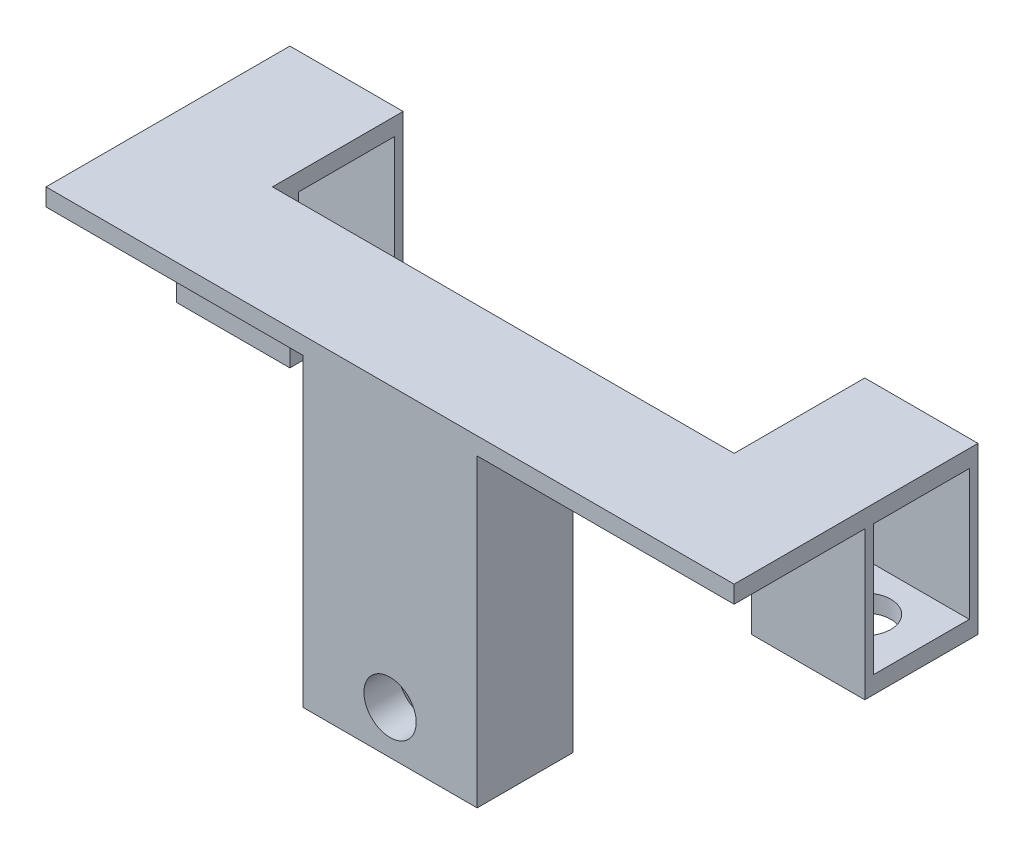
SolidWorks part; units mm, degrees
ref_plane "Front Plane" through (0, 0, 0) normal (0, 0, 1) x (1, 0, 0)
ref_plane "Top Plane" through (0, 0, 0) normal (0, 1, 0) x (1, 0, 0)
ref_plane "Right Plane" through (0, 0, 0) normal (1, 0, 0) x (0, 0, -1)
sketch "ｽｹｯﾁ2" plane through (0, 0, 0) normal (0, 1, 0) x (1, 0, 0)
  line L0 (6.5, 13) -> (6.5, 0) construction
  line L1 (0, 0) -> (13, 0)
  line L2 (0, 0) -> (0, 13)
  line L3 (0, 13) -> (13, 13)
  line L4 (13, 0) -> (13, 13)
  line L9 (39.5, 31.8136) -> (39.5, -25.5918) construction
  line L10 (0, 6.5) -> (13, 6.5) construction
  line L11 (79, 13) -> (66, 13)
  line L12 (66, 0) -> (66, 13)
  line L13 (79, 0) -> (66, 0)
  line L14 (79, 0) -> (79, 13)
  circle A2 centre (6.5, 6.5) radius 3
  circle A3 centre (72.5, 6.5) radius 3
  dimension "D5" = 6
  dimension "D1" = 13
  dimension "D2" = 13
  dimension "D3" = 33
extrude "ﾎﾞｽ - 押し出し1" add sketch "ｽｹｯﾁ2" along normal blind 2
sketch "ｽｹｯﾁ3" plane through (0, 2, 0) normal (0, 1, 0) x (1, 0, 0)
  line L0 (13, 0) -> (13, 13) construction
  line L1 (0, 13) -> (13, 13)
  line L2 (0, 13) -> (0, 12)
  line L3 (0, 12) -> (13, 12)
  line L4 (13, 13) -> (13, 12)
  line L5 (0, 6.5) -> (79, 6.5) construction
  line L6 (0, 13) -> (0, 0) construction
  line L7 (79, 0) -> (79, 13) construction
  line L8 (39.5, 6.5) -> (39.5, 29.5661) construction
  line L9 (0, 1) -> (13, 1)
  line L10 (13, 0) -> (13, 1)
  line L11 (0, 0) -> (13, 0)
  line L12 (0, 0) -> (0, 1)
  line L13 (79, 0) -> (79, 1)
  line L14 (79, 0) -> (66, 0)
  line L15 (66, 0) -> (66, 1)
  line L16 (79, 1) -> (66, 1)
  line L17 (79, 12) -> (66, 12)
  line L18 (66, 13) -> (66, 12)
  line L19 (79, 13) -> (66, 13)
  line L20 (79, 13) -> (79, 12)
  dimension "D1" = 1
extrude "ﾎﾞｽ - 押し出し2" add sketch "ｽｹｯﾁ3" along normal blind 15
sketch "ｽｹｯﾁ4" plane through (0, 17, 0) normal (0, 1, 0) x (1, 0, 0)
  line L0 (0, 13) -> (0, 0)
  line L1 (0, 0) -> (0, -15)
  line L2 (79, 13) -> (79, 0)
  line L3 (79, 0) -> (79, -15)
  line L4 (79, -15) -> (0, -15)
  line L5 (13, 0) -> (13, -2)
  line L6 (66, 0) -> (66, -2)
  line L7 (66, -2) -> (13, -2)
  line L8 (13, 0) -> (13, 13)
  line L9 (66, 1) -> (66, 12)
  line L10 (79, 13) -> (66, 13)
  line L11 (66, 13) -> (66, 12)
  line L12 (0, 13) -> (13, 13)
  line L14 (0, -15) -> (13, -15)
  line L15 (0, -15) -> (0, 13)
  line L16 (0, 13) -> (13, 13)
  line L17 (13, -15) -> (13, 13)
  line L18 (79, 13) -> (66, 13)
  line L19 (79, 13) -> (79, -15)
  line L20 (79, -15) -> (66, -15)
  line L21 (66, 13) -> (66, -15)
  line L22 (66, -2) -> (13, -2)
  line L23 (66, -2) -> (66, -15)
  line L24 (66, -15) -> (13, -15)
  line L25 (13, -2) -> (13, -15)
  line M6 (0, 1) -> (0, 0)
  line M7 (0, 0) -> (13, 0)
  line M8 (13, 0) -> (13, 1)
  line M9 (13, 1) -> (0, 1)
  dimension "D1" = 15
  dimension "D2" = 2
extrude "ﾎﾞｽ - 押し出し3" add sketch "ｽｹｯﾁ4" along normal blind 2 contours L4 L17 L5 L1 M7 | L12 L0 L8 M9 | M9 M6 M7 M8 | L21 L7 L17 L4 | L9 L21 L6 L4 L3 L2 L10 L11
sketch "ｽｹｯﾁ5" plane through (0, 17, 0) normal (0, -1, 0) x (1, 0, 0)
  line L0 (66, 2) -> (13, 2) construction
  line L1 (49.5, 2) -> (29.5, 2)
  line L2 (49.5, 2) -> (49.5, 15)
  line L3 (49.5, 15) -> (29.5, 15)
  line L4 (29.5, 2) -> (29.5, 15)
  line L5 (79, 15) -> (0, 15) construction
  line L7 (49.5, 15) -> (29.5, 15)
  line L8 (49.5, 15) -> (49.5, 4)
  line L9 (49.5, 4) -> (29.5, 4)
  line L10 (29.5, 15) -> (29.5, 4)
  line L11 (13, 2) -> (13, -13) construction
  line L13 (66, 2) -> (66, -13) construction
  line M11 (79, 15) -> (0, 15)
  dimension "D1" = 20
  dimension "D2" = 11
  dimension "D3" = 16.5
  dimension "D4" = 16.5
extrude "ﾎﾞｽ - 押し出し4" add sketch "ｽｹｯﾁ5" along normal blind 37 contours L9 L2 L4 M11
sketch "ｽｹｯﾁ6" plane through (0, 0, 4) normal (0, 0, -1) x (-1, 0, 0)
  line L0 (-39.5, -20) -> (-39.5, 23.0284) construction
  line L1 (-49.5, -20) -> (-29.5, -20) construction
  circle A1 centre (-39.5, -13) radius 3
  dimension "D1" = 6
  dimension "D2" = 7
extrude "ｶｯﾄ - 押し出し1" cut sketch "ｽｹｯﾁ6" against normal through all both and the other way through all
sketch "ｽｹｯﾁ7" plane through (0, -20, 0) normal (0, -1, 0) x (1, 0, 0)
  line L0 (49.5, 4) -> (49.5, 15) construction
  line L1 (43.5, 6) -> (35.5, 6)
  line L2 (43.5, 6) -> (43.5, 11)
  line L3 (43.5, 11) -> (35.5, 11)
  line L4 (35.5, 6) -> (35.5, 11)
  line L5 (49.5, 15) -> (29.5, 15) construction
  dimension "D1" = 5
  dimension "D2" = 8
  dimension "D3" = 6
  dimension "D4" = 4
extrude "ｶｯﾄ - 押し出し2" cut sketch "ｽｹｯﾁ7" against normal blind 17
sketch "ｽｹｯﾁ8" plane through (0, -20, 0) normal (0, -1, 0) x (1, 0, 0)
  line L1 (29.5, 15) -> (49.5, 15)
  line L2 (29.5, 15) -> (29.5, 4)
  line L3 (29.5, 4) -> (49.5, 4)
  line L4 (49.5, 15) -> (49.5, 4)
extrude "ｶｯﾄ - 押し出し3" cut sketch "ｽｹｯﾁ8" against normal blind 2
